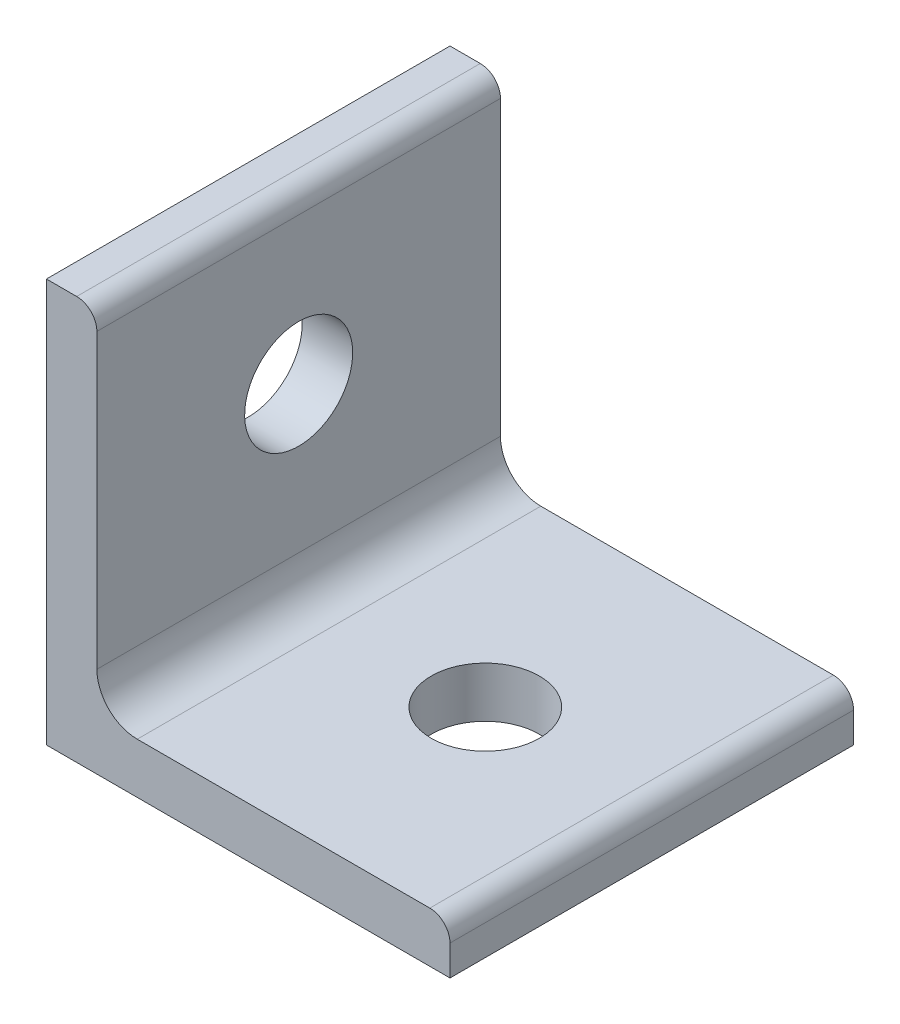
SolidWorks part; units mm, degrees
ref_plane "Front Plane" through (0, 0, 0) normal (0, 0, 1) x (1, 0, 0)
ref_plane "Top Plane" through (0, 0, 0) normal (0, 1, 0) x (1, 0, 0)
ref_plane "Right Plane" through (0, 0, 0) normal (1, 0, 0) x (0, 0, -1)
sketch "Sketch1" plane through (0, 0, 0) normal (0, 0, 1) x (1, 0, 0)
  line L0 (0, 0) -> (0, 12.7)
  line L1 (1.5875, 12.7) -> (1.5875, 1.5875)
  line L2 (1.5875, 1.5875) -> (12.7, 1.5875)
  line L3 (12.7, 1.5875) -> (12.7, 0)
  line L4 (12.7, 0) -> (0, 0)
  line L5 (1.5875, 12.7) -> (0, 12.7)
  dimension "D1" = 12.7
  dimension "D2" = 12.7
  dimension "D3" = 1.5875
  dimension "D4" = 1.5875
extrude "Boss-Extrude1" add sketch "Sketch1" along normal blind 12.7
fillet "Fillet1" radius 1.27 1 edges at (1.5875, 1.5875, 6.35)
fillet "Fillet2" radius 0.635 2 edges at (12.7, 1.5875, 6.35) (1.5875, 12.7, 6.35)
sketch "Sketch2" plane through (1.5875, 0, 0) normal (1, 0, 0) x (0, 0, -1)
  line L0 (-12.7, 7.4612) -> (-6.35, 7.4612) construction
  line L1 (-12.7, 2.8575) -> (-12.7, 12.065) construction
  line L2 (-6.35, 7.4612) -> (0, 7.4612) construction
  line L3 (0, 2.8575) -> (0, 12.065) construction
  circle A0 centre (-6.35, 7.4612) radius 1.7
  dimension "D1" = 3.4
extrude "Cut-Extrude1" cut sketch "Sketch2" against normal through all
sketch "Sketch3" plane through (0, 1.5875, 0) normal (0, 1, 0) x (1, 0, 0)
  line L0 (7.4612, 0) -> (7.4612, -6.35) construction
  line L1 (12.065, 0) -> (2.8575, 0) construction
  line L2 (7.4612, -6.35) -> (7.4613, -12.7) construction
  line L3 (12.065, -12.7) -> (2.8575, -12.7) construction
  circle A0 centre (7.4612, -6.35) radius 1.7
  dimension "D1" = 3.4
extrude "Cut-Extrude2" cut sketch "Sketch3" against normal through all
